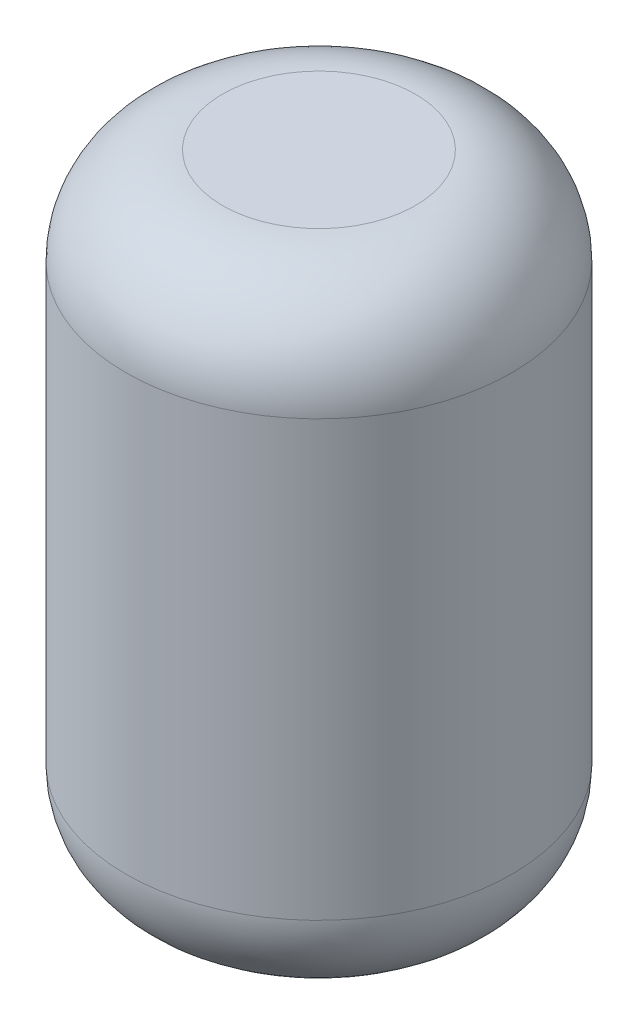
SolidWorks part; units mm, degrees
material "Custom Plastic"
ref_plane "Front Plane" through (0, 0, 0) normal (0, 0, 1) x (1, 0, 0)
ref_plane "Top Plane" through (0, 0, 0) normal (0, 1, 0) x (1, 0, 0)
ref_plane "Right Plane" through (0, 0, 0) normal (1, 0, 0) x (0, 0, -1)
sketch "Sketch1" plane through (0, 0, 0) normal (0, 1, 0) x (1, 0, 0)
  circle A0 centre (0, 0) radius 50.8
  dimension "D1" = 101.6
extrude "Boss-Extrude1" add sketch "Sketch1" along normal blind 165.1
fillet "Fillet1" radius 25.4 1 edges at (0, 165.1, 50.8)
fillet "Fillet2" radius 25.4 1 edges at (0, 0, 50.8)
